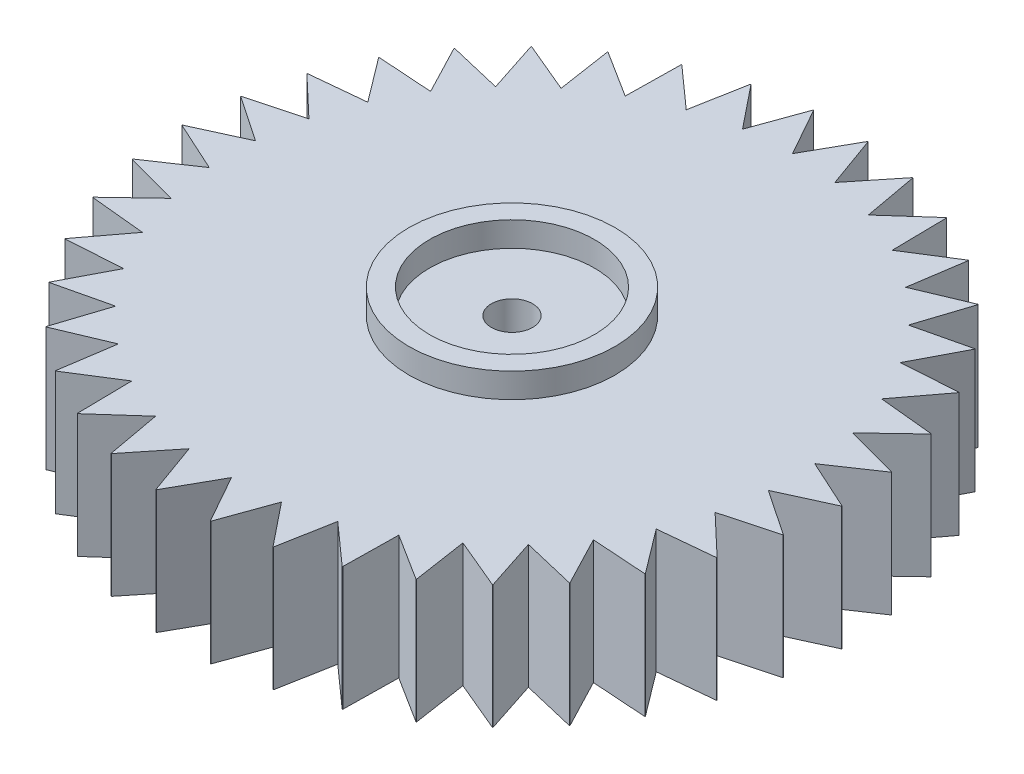
SolidWorks part; units mm, degrees
ref_plane "Alzado" through (0, 0, 0) normal (0, 0, 1) x (1, 0, 0)
ref_plane "Planta" through (0, 0, 0) normal (0, 1, 0) x (1, 0, 0)
ref_plane "Vista lateral" through (0, 0, 0) normal (1, 0, 0) x (0, 0, -1)
sketch "Croquis1" plane through (0, 0, 0) normal (0, 1, 0) x (1, 0, 0)
  circle A0 centre (0, 0) radius 40
extrude "Saliente-Extruir1" add sketch "Croquis1" along normal blind 15
sketch "Croquis2" plane through (0, 0, 0) normal (0, 1, 0) x (1, 0, 0)
  line L0 (0, 40) -> (0, 0)
  line L1 (0, 34.026) -> (3.2769, 39.8655)
  line L2 (3.2769, 39.8655) -> (0, 41.7044)
  line L3 (0, 41.7044) -> (-3.2769, 39.8655)
  line L4 (-3.2769, 39.8655) -> (0, 34.026)
  circle A0 centre (0, 0) radius 40 construction
extrude "Cortar-Extruir3" cut sketch "Croquis2" along normal blind 20 and the other way blind 55 contours L1 L2 L3 L4
pattern_circular "MatrizC1" count 38 over 360 about axis through (0, 0, 0) along (0, 1, 0) of "Cortar-Extruir3"
sketch "Croquis4" plane through (0, 0, 0) normal (0, 1, 0) x (1, 0, 0)
  circle A0 centre (0, 0) radius 12.5
  circle A1 centre (0, 0) radius 10
extrude "Saliente-Extruir2" add sketch "Croquis4" along normal blind 18 and the other way blind 3
sketch "Croquis5" plane through (0, 0, 0) normal (0, 1, 0) x (1, 0, 0)
  circle A0 centre (0, 0) radius 2.5
extrude "Cortar-Extruir4" cut sketch "Croquis5" along normal blind 26 and the other way blind 41
